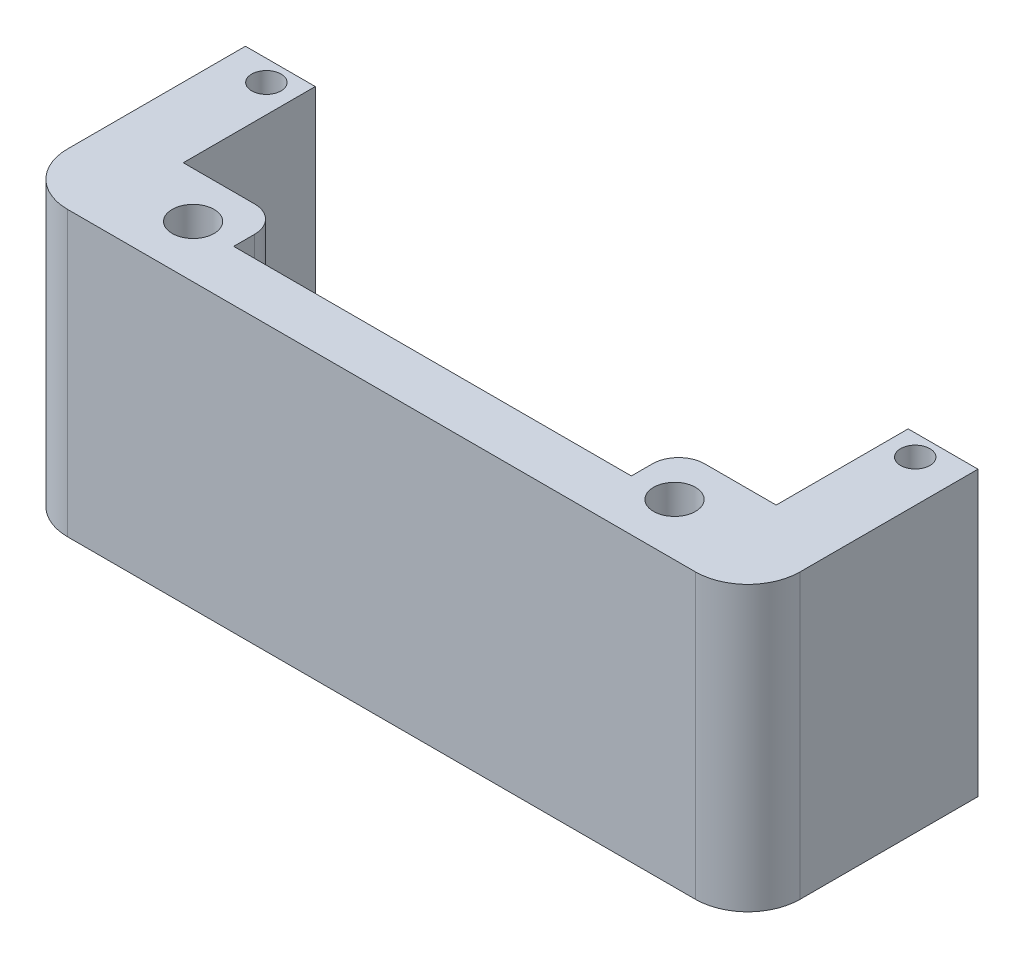
SolidWorks part; units mm, degrees
ref_plane "Front Plane" through (0, 0, 0) normal (0, 0, 1) x (1, 0, 0)
ref_plane "Top Plane" through (0, 0, 0) normal (0, 1, 0) x (1, 0, 0)
ref_plane "Right Plane" through (0, 0, 0) normal (1, 0, 0) x (0, 0, -1)
sketch "Sketch1" plane through (0, 0, 0) normal (0, 1, 0) x (1, 0, 0)
  line L0 (0, -64.962) -> (0, 64.962)
  line L1 (-38, -6.3014) -> (38, -6.3014)
  line L2 (38, -6.3014) -> (38, 27.9486)
  line L3 (-38, -6.3014) -> (-38, 27.9486)
  line L4 (38, 27.9486) -> (70, 27.9486)
  line L5 (-38, 27.9486) -> (-70, 27.9486)
  line L6 (70, 27.9486) -> (70, -16.0514)
  line L7 (-70, 27.9486) -> (-70, -16.0514)
  line L8 (70, -16.0514) -> (-70, -16.0514)
  line L9 (-70, 27.9486) -> (-37.0457, 27.9486)
  spline S0 degree 2 poles (38, -6.3014) (37.4717, -6.3148) (36.9264, -6.3014) knots 0.972384 0.972384 0.972384 1 1 1
  point P4 (0, 0)
  point P8 (0, -6.3014)
  point P15 (0, -16.0514)
  dimension "D1" = 140
  dimension "D2" = 44
  dimension "D3" = 32
  dimension "D4" = 34.25
extrude "Boss-Extrude1" add sketch "Sketch1" along normal blind 54.2 contours L8 L0 L1 L3 L5 L7 | L8 L6 L4 L2 L1 L0
fillet "Fillet1" radius 10 2 edges at (70, 27.1, 16.0514) (-70, 27.1, 16.0514)
sketch "Sketch2" plane through (0, 54.2, 0) normal (0, 1, 0) x (1, 0, 0)
  spline S0 degree 3 poles (62, 25.9486) (58, 25.9486) (58, 21.9486) (62, 21.9486) (66, 21.9486) (66, 25.9486) (62, 25.9486) (58, 25.9486) (58, 21.9486) knots -0.5 0 0 0 0.5 0.5 0.5 1 1 1 1.5 1.5 1.5 weights 1 0.333333 0.333333 1 0.333333 0.333333 1 0.333333 0.333333 only from (62, 25.9486) to (62, 25.9486) construction
  spline S2 degree 3 poles (45.9972, -10.0514) (53.9972, -10.057) (54.0028, -2.057) (46.0028, -2.0514) (38.0028, -2.0458) (37.9972, -10.0458) (45.9972, -10.0514) (53.9972, -10.057) (54.0028, -2.057) knots -0.5 0 0 0 0.5 0.5 0.5 1 1 1 1.5 1.5 1.5 weights 1 0.333333 0.333333 1 0.333333 0.333333 1 0.333333 0.333333 only from (45.9972, -10.0514) to (45.9972, -10.0514) construction
  spline S3 degree 3 poles (-50, -6.0486) (-50.0056, -14.0486) (-42.0056, -14.0542) (-42, -6.0542) (-41.9944, 1.9458) (-49.9944, 1.9514) (-50, -6.0486) (-50.0056, -14.0486) (-42.0056, -14.0542) knots -0.5 0 0 0 0.5 0.5 0.5 1 1 1 1.5 1.5 1.5 weights 1 0.333333 0.333333 1 0.333333 0.333333 1 0.333333 0.333333 only from (-50, -6.0486) to (-50, -6.0486) construction
  spline S5 degree 3 poles (-62, 21.9486) (-58, 21.9486) (-58, 25.9486) (-62, 25.9486) (-66, 25.9486) (-66, 21.9486) (-62, 21.9486) (-58, 21.9486) (-58, 25.9486) knots -0.5 0 0 0 0.5 0.5 0.5 1 1 1 1.5 1.5 1.5 weights 1 0.333333 0.333333 1 0.333333 0.333333 1 0.333333 0.333333 only from (-62, 21.9486) to (-62, 21.9486) construction
  spline S6 degree 3 poles (62, 25.9486) (58, 25.9486) (58, 21.9486) (62, 21.9486) (66, 21.9486) (66, 25.9486) (62, 25.9486) (58, 25.9486) (58, 21.9486) knots -0.5 0 0 0 0.5 0.5 0.5 1 1 1 1.5 1.5 1.5 weights 1 0.333333 0.333333 1 0.333333 0.333333 1 0.333333 0.333333 only from (62, 25.9486) to (62, 25.9486)
  spline S8 degree 3 poles (45.9972, -10.0514) (53.9972, -10.057) (54.0028, -2.057) (46.0028, -2.0514) (38.0028, -2.0458) (37.9972, -10.0458) (45.9972, -10.0514) (53.9972, -10.057) (54.0028, -2.057) knots -0.5 0 0 0 0.5 0.5 0.5 1 1 1 1.5 1.5 1.5 weights 1 0.333333 0.333333 1 0.333333 0.333333 1 0.333333 0.333333 only from (45.9972, -10.0514) to (45.9972, -10.0514)
  spline S9 degree 3 poles (-50, -6.0486) (-50.0056, -14.0486) (-42.0056, -14.0542) (-42, -6.0542) (-41.9944, 1.9458) (-49.9944, 1.9514) (-50, -6.0486) (-50.0056, -14.0486) (-42.0056, -14.0542) knots -0.5 0 0 0 0.5 0.5 0.5 1 1 1 1.5 1.5 1.5 weights 1 0.333333 0.333333 1 0.333333 0.333333 1 0.333333 0.333333 only from (-50, -6.0486) to (-50, -6.0486)
  spline S11 degree 3 poles (-62, 21.9486) (-58, 21.9486) (-58, 25.9486) (-62, 25.9486) (-66, 25.9486) (-66, 21.9486) (-62, 21.9486) (-58, 21.9486) (-58, 25.9486) knots -0.5 0 0 0 0.5 0.5 0.5 1 1 1 1.5 1.5 1.5 weights 1 0.333333 0.333333 1 0.333333 0.333333 1 0.333333 0.333333 only from (-62, 21.9486) to (-62, 21.9486)
extrude "Cut-Extrude1" cut sketch "Sketch2" against normal blind 54.2
sketch "Sketch4" plane through (0, 54.2, 0) normal (0, 1, 0) x (1, 0, 0)
  line L0 (0, -16.0514) -> (0, 33.2153) construction
  line L1 (60, -16.0514) -> (-60, -16.0514) construction
  line L2 (38, 2.7226) -> (56.6546, 2.7226)
  line L3 (38, -6.3014) -> (38, 27.9486) construction
  line L4 (-38, 2.7226) -> (-56.6546, 2.7226)
  line L5 (56.6546, 2.7226) -> (56.6546, 27.9486)
  line L6 (38, 27.9486) -> (70, 27.9486) construction
  line L7 (-56.6546, 2.7226) -> (-56.6546, 27.9486)
  line L8 (56.6546, 27.9486) -> (38, 27.9486)
  line L9 (-56.6546, 27.9486) -> (-38, 27.9486)
  line L10 (38, 27.9486) -> (38, 2.7226)
  line L11 (-38, 27.9486) -> (-38, 2.7226)
  line M9 (-38, 27.9486) -> (-70, 27.9486)
  line M17 (70, 27.9486) -> (38, 27.9486)
  line M18 (38, 27.9486) -> (38, -6.3014)
  line M21 (-38, -6.3014) -> (-38, 27.9486)
extrude "Cut-Extrude2" cut sketch "Sketch4" against normal blind 54.2 contours L7 L4 M21 M9 | L2 L5 M17 M18
fillet "Fillet3" radius 5 2 edges at (38, 27.1, -2.7226) (-38, 27.1, -2.7226)
sketch "Sketch5" plane through (0, 54.2, 0) normal (0, 1, 0) x (1, 0, 0)
  circle A0 centre (-62, 23.9486) radius 2.8
  circle A1 centre (62, 23.9486) radius 2.8
  dimension "D1" = 5.6
  dimension "D2" = 5.6
extrude "Cut-Extrude3" cut sketch "Sketch5" against normal through all
